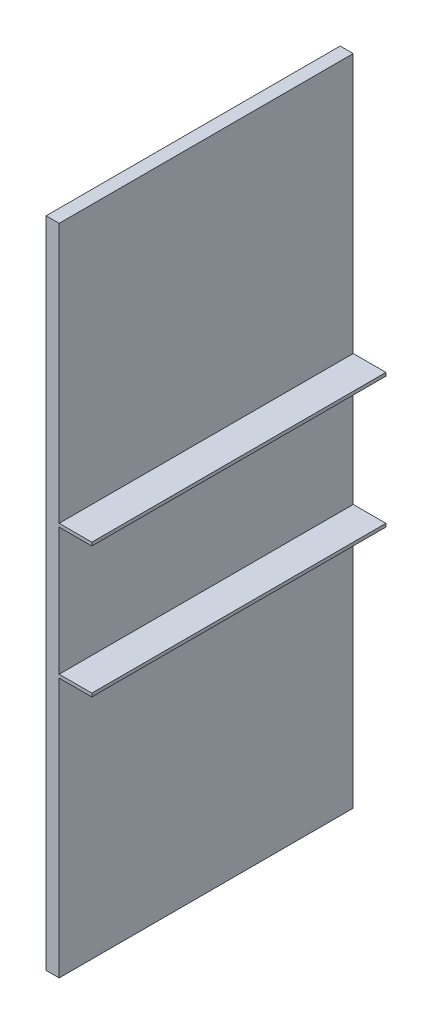
SolidWorks part; units mm, degrees
ref_plane "Front Plane" through (0, 0, 0) normal (0, 0, 1) x (1, 0, 0)
ref_plane "Top Plane" through (0, 0, 0) normal (0, 1, 0) x (1, 0, 0)
ref_plane "Right Plane" through (0, 0, 0) normal (1, 0, 0) x (0, 0, -1)
sketch "Sketch1" plane through (0, 0, 0) normal (0, 1, 0) x (1, 0, 0)
  line L1 (-7, 45) -> (7, 45)
  line L2 (-7, 45) -> (-7, -45)
  line L3 (-7, -45) -> (7, -45)
  line L4 (7, 45) -> (7, -45)
  line L5 (-7, 45) -> (7, -45) construction
  line L6 (-7, -45) -> (7, 45) construction
  point P0 (0, 0)
  dimension "D1" = 90
  dimension "D2" = 14
extrude "Boss-Extrude1" add sketch "Sketch1" along normal blind 200
sketch "Sketch2" plane through (0, 200, 0) normal (0, 1, 0) x (1, 0, 0)
  line L0 (-7, -45) -> (7, -45) construction
  line L1 (7, 45) -> (-3, 45)
  line L2 (7, 45) -> (7, -45)
  line L3 (7, -45) -> (-3, -45)
  line L4 (-3, 45) -> (-3, -45)
  line L5 (-7, 45) -> (-7, -45) construction
  dimension "D1" = 4
extrude "Cut-Extrude1" cut sketch "Sketch2" against normal through all
sketch "Sketch3" plane through (-3, 0, 0) normal (1, 0, 0) x (0, 0, -1)
  line L0 (-45, 0) -> (-45, 200) construction
  line L1 (-45, 120.5) -> (45, 120.5)
  line L2 (-45, 120.5) -> (-45, 119.5)
  line L3 (-45, 119.5) -> (45, 119.5)
  line L4 (45, 120.5) -> (45, 119.5)
  line L5 (45, 0) -> (45, 200) construction
  line L6 (45, 200) -> (-45, 200) construction
  line L7 (45, 0) -> (-45, 0) construction
  line L8 (-45, 79.5) -> (45, 79.5)
  line L9 (-45, 79.5) -> (-45, 80.5)
  line L10 (-45, 80.5) -> (45, 80.5)
  line L11 (45, 79.5) -> (45, 80.5)
  dimension "D1" = 1
  dimension "D2" = 79.5
  dimension "D3" = 1
  dimension "D4" = 79.5
extrude "Boss-Extrude2" add sketch "Sketch3" along normal blind 10
